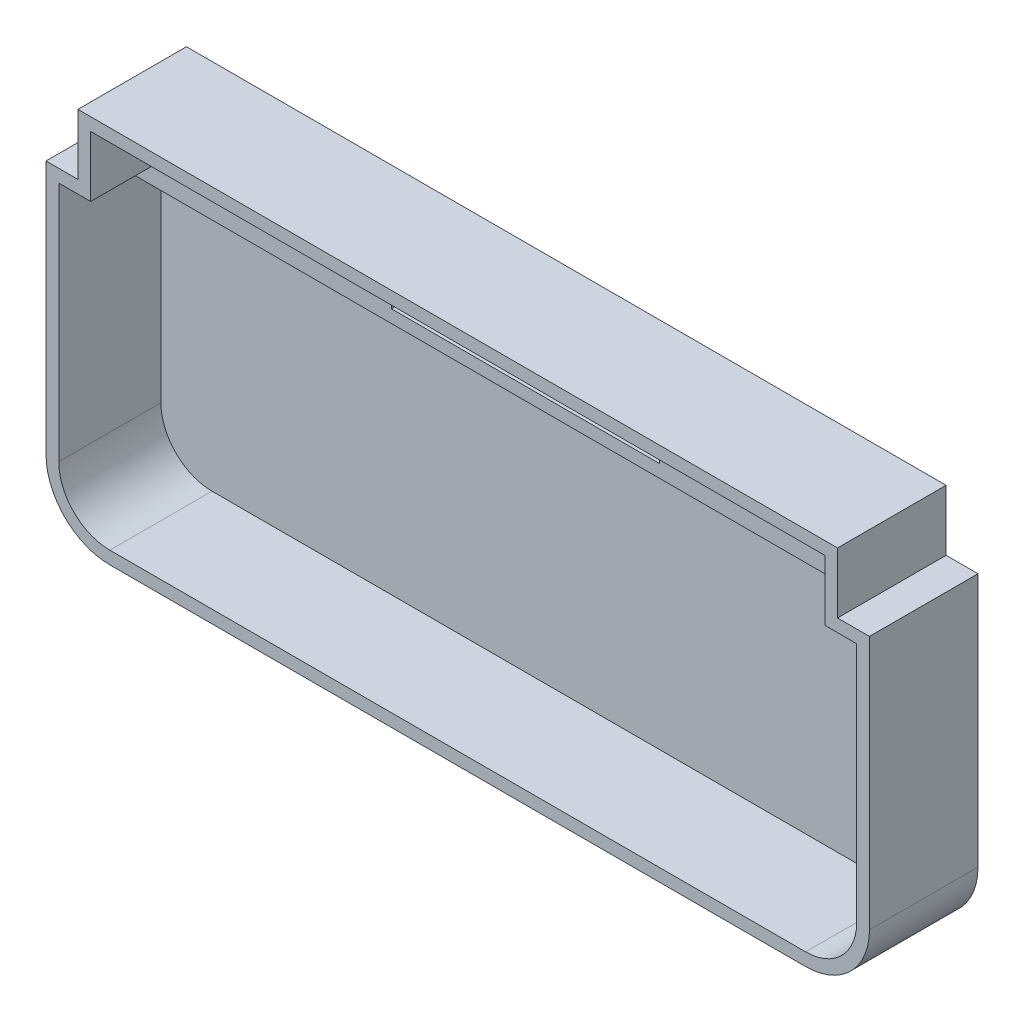
SolidWorks part; units mm, degrees
material "ABS"
ref_plane "Top Plane" through (0, 0, 0) normal (0, 0, 1) x (1, 0, 0)
ref_plane "Front Plane" through (0, 0, 0) normal (0, 1, 0) x (1, 0, 0)
ref_plane "Right Plane" through (0, 0, 0) normal (1, 0, 0) x (0, 0, -1)
sketch "Sketch1" plane through (0, 0, 0) normal (0, 0, 1) x (1, 0, 0)
  line L0 (-59.5, 15) -> (59.5, 15)
  line L7 (59.5, 15) -> (59.5, 5.5)
  line L8 (59.5, 5.5) -> (64.5, 5.5)
  line L9 (64.5, 5.5) -> (64.5, -44.3)
  line L10 (64.5, -44.3) -> (-64.5, -44.3)
  line L11 (-64.5, -44.3) -> (-64.5, 5.5)
  line L12 (-64.5, 5.5) -> (-59.5, 5.5)
  line L13 (-59.5, 5.5) -> (-59.5, 15)
  point P0 (0, 0)
  dimension "D1" = 119
  dimension "D2" = 59.3
  dimension "D3" = 9.5
  dimension "D4" = 5
  dimension "D5" = 5
  dimension "D6" = 9.5
extrude "Boss-Extrude1" add sketch "Sketch1" along normal blind 1
fillet "Fillet1" radius 10 2 edges at (64.5, -44.3, 0.5) (-64.5, -44.3, 0.5)
sketch "Sketch2" plane through (0, 0, 1) normal (0, 0, 1) x (1, 0, 0)
  line L24 (59.5, 5.5) -> (59.5, 15)
  line L25 (59.5, 15) -> (-59.5, 15)
  line L26 (-59.5, 15) -> (-59.5, 5.5)
  line L27 (-59.5, 5.5) -> (-64.5, 5.5)
  line L28 (-64.5, 5.5) -> (-64.5, -34.3)
  line L29 (-54.5, -44.3) -> (54.5, -44.3)
  line L30 (64.5, -34.3) -> (64.5, 5.5)
  line L31 (64.5, 5.5) -> (59.5, 5.5)
  line L32 (59.5, 5.5) -> (59.5, 15)
  line L33 (59.5, 15) -> (-59.5, 15)
  line L34 (-59.5, 15) -> (-59.5, 5.5)
  line L35 (-59.5, 5.5) -> (-64.5, 5.5)
  line L36 (-64.5, 5.5) -> (-64.5, -34.3)
  line L37 (-54.5, -44.3) -> (54.5, -44.3)
  line L38 (64.5, -34.3) -> (64.5, 5.5)
  line L39 (64.5, 5.5) -> (59.5, 5.5)
  line L48 (-54.5, -42.3) -> (54.5, -42.3)
  line L49 (62.5, -34.3) -> (62.5, 3.5)
  line L50 (62.5, 3.5) -> (57.5, 3.5)
  line L51 (57.5, 3.5) -> (57.5, 13)
  line L52 (57.5, 13) -> (-57.5, 13)
  line L53 (-57.5, 13) -> (-57.5, 3.5)
  line L54 (-57.5, 3.5) -> (-62.5, 3.5)
  line L55 (-62.5, 3.5) -> (-62.5, -34.3)
  line L56 (-54.5, -42.3) -> (54.5, -42.3)
  line L57 (62.5, -34.3) -> (62.5, 3.5)
  line L58 (62.5, 3.5) -> (57.5, 3.5)
  line L59 (57.5, 3.5) -> (57.5, 13)
  line L60 (57.5, 13) -> (-57.5, 13)
  line L61 (-57.5, 13) -> (-57.5, 3.5)
  line L62 (-57.5, 3.5) -> (-62.5, 3.5)
  line L63 (-62.5, 3.5) -> (-62.5, -34.3)
  arc A2 (54.5, -44.3) -> (64.5, -34.3) centre (54.5, -34.3) ccw
  arc A3 (54.5, -44.3) -> (64.5, -34.3) centre (54.5, -34.3) ccw
  arc A4 (-64.5, -34.3) -> (-54.5, -44.3) centre (-54.5, -34.3) ccw
  arc A5 (-64.5, -34.3) -> (-54.5, -44.3) centre (-54.5, -34.3) ccw
  arc A8 (54.5, -42.3) -> (62.5, -34.3) centre (54.5, -34.3) ccw
  arc A9 (-62.5, -34.3) -> (-54.5, -42.3) centre (-54.5, -34.3) ccw
  arc A10 (54.5, -42.3) -> (62.5, -34.3) centre (54.5, -34.3) ccw
  arc A11 (-62.5, -34.3) -> (-54.5, -42.3) centre (-54.5, -34.3) ccw
  dimension "D1" = 0
  dimension "D2" = 2
extrude "Boss-Extrude2" add sketch "Sketch2" along normal blind 16
sketch "Sketch3" plane through (0, 0, 1) normal (0, 0, 1) x (1, 0, 0)
  line L2 (-20.8775, 2) -> (21.1225, 2)
  line L31 (21.1225, 2) -> (21.1225, 13)
  line L32 (-20.8775, 2) -> (-20.8775, 13)
  line L33 (21.1225, 13) -> (57.5, 13)
  line L34 (57.5, 13) -> (57.5, 3.5)
  line L35 (57.5, 3.5) -> (62.5, 3.5)
  line L36 (62.5, 3.5) -> (62.5, 0)
  line L37 (62.5, -34.3) -> (62.5, 3.5) construction
  line L38 (62.5, 0) -> (-62.5, 0)
  line L39 (-62.5, 3.5) -> (-62.5, -34.3) construction
  line L40 (-62.5, 0) -> (-62.5, 3.5)
  line L41 (-62.5, 3.5) -> (-57.5, 3.5)
  line L44 (-57.5, 3.5) -> (-57.5, 13)
  line L45 (-57.5, 13) -> (-20.8775, 13)
  point P9 (0, 0)
  point P12 (0, 0)
  dimension "D1" = 42
  dimension "D2" = 11
  dimension "D3" = 11
extrude "Boss-Extrude3" add sketch "Sketch3" along normal blind 5.5
